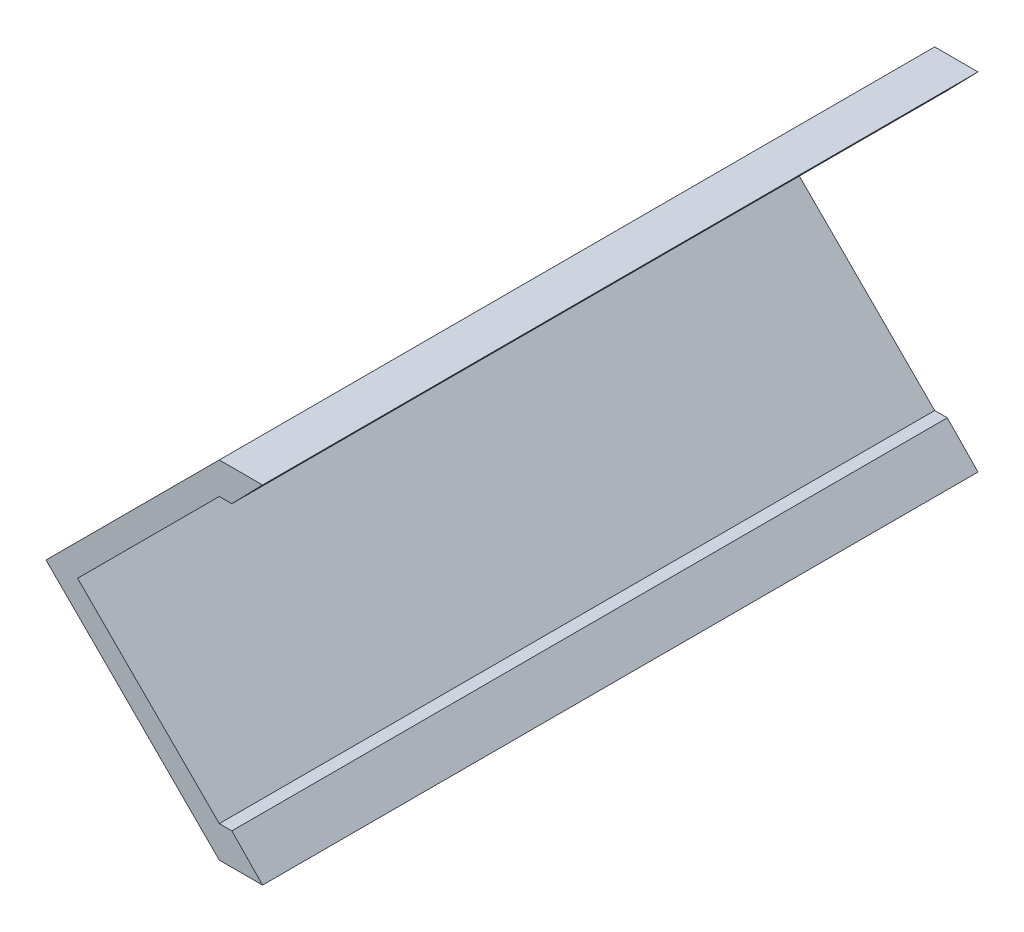
SolidWorks part; units mm, degrees
ref_plane "Front Plane" through (0, 0, 0) normal (0, 0, 1) x (1, 0, 0)
ref_plane "Top Plane" through (0, 0, 0) normal (0, 1, 0) x (1, 0, 0)
ref_plane "Right Plane" through (0, 0, 0) normal (1, 0, 0) x (0, 0, -1)
sketch "Sketch1" plane through (0, 0, 0) normal (0, 0, 1) x (1, 0, 0)
  line L0 (22, 0) -> (34.4, -12.4)
  line L1 (34.4, -12.4) -> (37.4975, -12.4)
  line L2 (37.4975, -12.4) -> (35.2997, -10.1373)
  line L3 (35.2997, -10.1373) -> (34.4, -10.1373)
  line L4 (34.4, -10.1373) -> (24.2627, 0)
  line L5 (24.2627, 0) -> (34.4, 10.1373)
  line L6 (34.4, 10.1373) -> (35.2997, 10.1373)
  line L7 (35.2997, 10.1373) -> (37.4975, 12.4)
  line L8 (37.4975, 12.4) -> (34.4, 12.4)
  line L9 (34.4, 12.4) -> (22, 0)
extrude "V_deflector" add sketch "Sketch1" along normal blind 51.2
